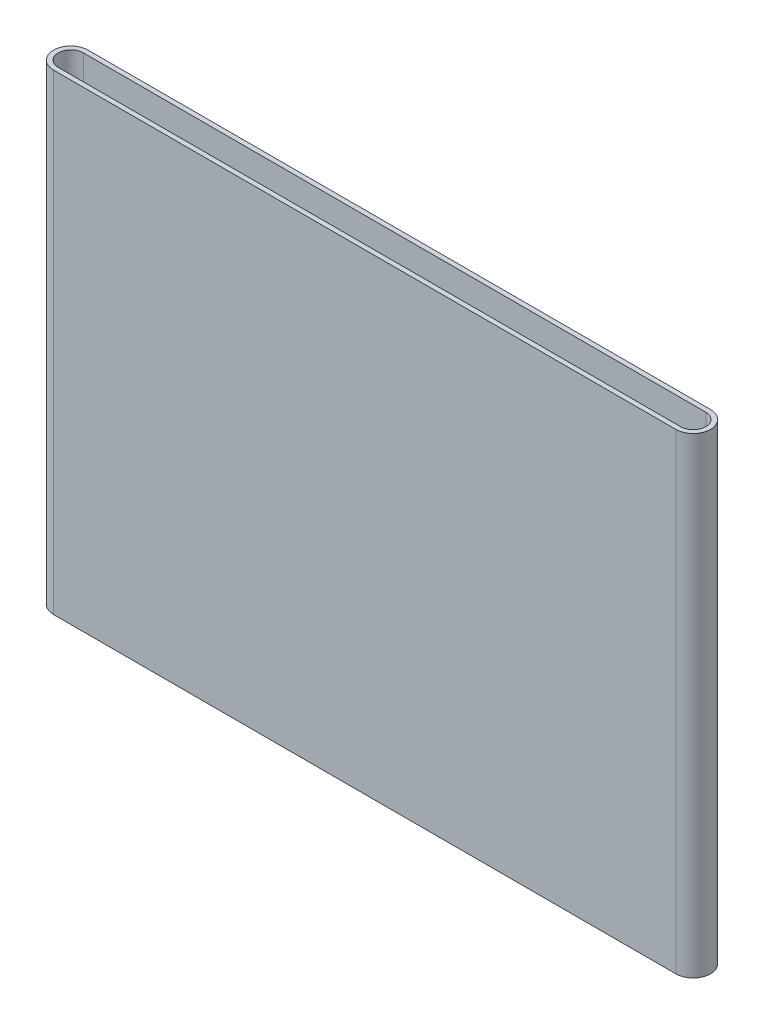
SolidWorks part; units mm, degrees
ref_plane "前视基准面" through (0, 0, 0) normal (0, 0, 1) x (1, 0, 0)
ref_plane "上视基准面" through (0, 0, 0) normal (0, 1, 0) x (1, 0, 0)
ref_plane "右视基准面" through (0, 0, 0) normal (1, 0, 0) x (0, 0, -1)
sketch "草图1" plane through (0, 0, 0) normal (0, 1, 0) x (1, 0, 0)
  line L0 (-99, -5.5) -> (99, -5.5)
  line L1 (-99, 4) -> (99, 4)
  line L2 (-99, 4) -> (-99, -4) construction
  line L3 (-99, -4) -> (99, -4)
  line L4 (99, 4) -> (99, -4) construction
  line L5 (-99, 4) -> (99, -4) construction
  line L6 (-99, -4) -> (99, 4) construction
  line L7 (-99, 5.5) -> (99, 5.5)
  arc A0 (-99, 4) -> (-99, -4) centre (-99, 0) ccw
  arc A1 (99, -4) -> (99, 4) centre (99, 0) ccw
  arc A2 (-99, 5.5) -> (-99, -5.5) centre (-99, 0) ccw
  arc A3 (99, -5.5) -> (99, 5.5) centre (99, 0) ccw
  point P0 (0, 0)
  dimension "D1" = 8
  dimension "D2" = 198
  dimension "D3" = 1.5
extrude "凸台-拉伸1" add sketch "草图1" along normal blind 150
